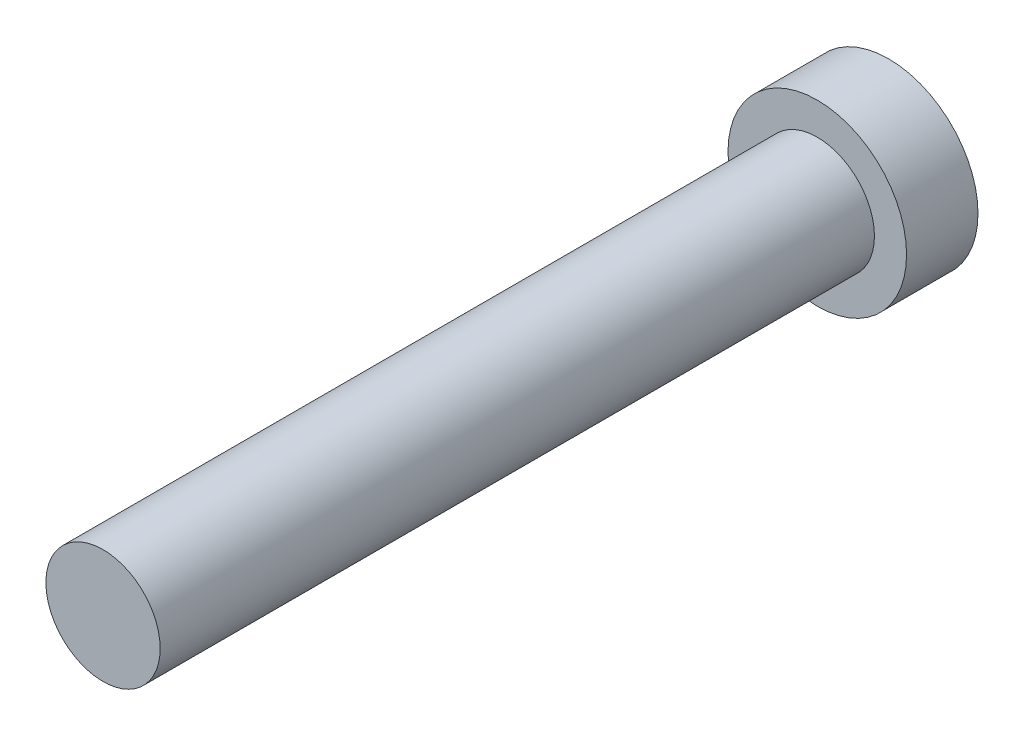
SolidWorks part; units mm, degrees
ref_plane "Front Plane" through (0, 0, 0) normal (0, 0, 1) x (1, 0, 0)
ref_plane "Top Plane" through (0, 0, 0) normal (0, 1, 0) x (1, 0, 0)
ref_plane "Right Plane" through (0, 0, 0) normal (1, 0, 0) x (0, 0, -1)
sketch "Sketch1" plane through (0, 0, 0) normal (0, 0, 1) x (1, 0, 0)
  circle A0 centre (0, 0) radius 1.6
  dimension "D1" = 3.2
extrude "Boss-Extrude1" add sketch "Sketch1" along normal mid plane 20
sketch "Sketch2" plane through (0, 0, -10) normal (0, 0, -1) x (-1, 0, 0)
  circle A0 centre (0, 0) radius 2.5
  dimension "D1" = 5
extrude "Boss-Extrude2" add sketch "Sketch2" along normal blind 2
